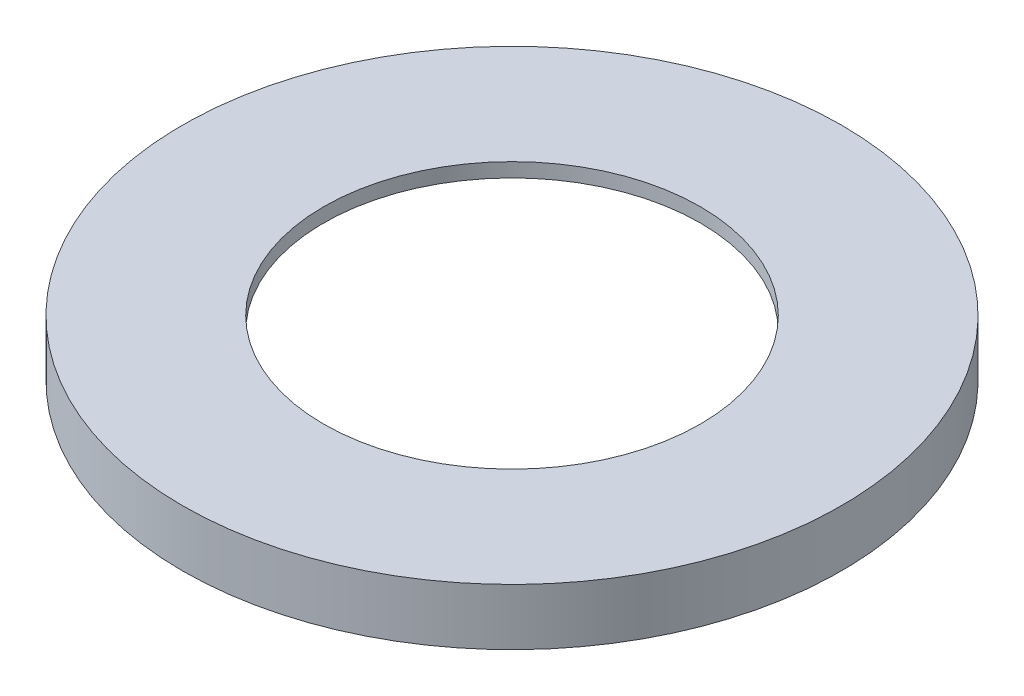
SolidWorks part; units mm, degrees
ref_plane "Front Plane" through (0, 0, 0) normal (0, 0, 1) x (1, 0, 0)
ref_plane "Top Plane" through (0, 0, 0) normal (0, 1, 0) x (1, 0, 0)
ref_plane "Right Plane" through (0, 0, 0) normal (1, 0, 0) x (0, 0, -1)
sketch "Sketch1" plane through (0, 0, 0) normal (0, 1, 0) x (1, 0, 0)
  circle A0 centre (0, 0) radius 35
  circle A1 centre (0, 0) radius 20
  dimension "D1" = 70
  dimension "D2" = 40
extrude "Boss-Extrude1" add sketch "Sketch1" along normal blind 6
sketch "Sketch2" plane through (0, 0, 0) normal (1, 0, 0) x (0, 0, -1)
  line L0 (-35, 0) -> (35, 0) construction
  line L1 (-20, 0) -> (-31, 0)
  line L2 (-20, 0) -> (-20, 4.5)
  line L3 (-20, 4.5) -> (-31, 4.5)
  line L4 (-31, 0) -> (-31, 4.5)
  line L5 (-20, 0) -> (20, 0) construction
  line L6 (-20, 0) -> (20, 0) construction
  line L7 (0, 0) -> (0, 13.052) construction
  dimension "D1" = 11
  dimension "D2" = 4.5
revolve "Cut-Revolve1" cut sketch "Sketch2" angle 360 about L7
